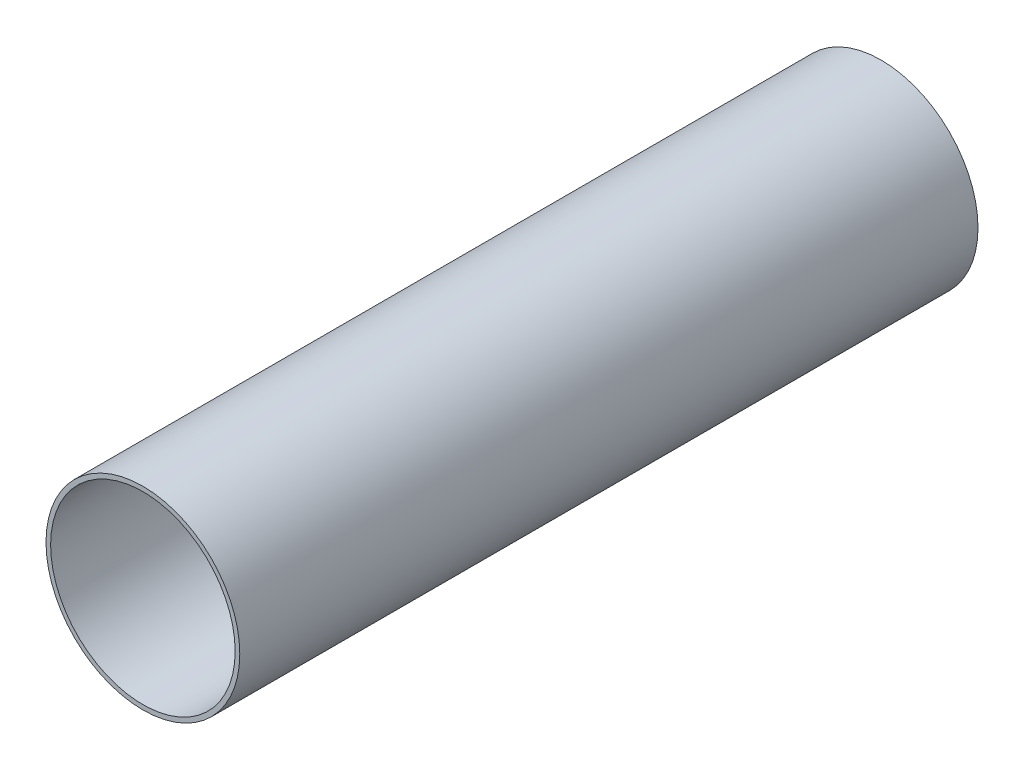
SolidWorks part; units mm, degrees
material "Corrugated Paper"
ref_plane "Front Plane" through (0, 0, 0) normal (0, 0, 1) x (1, 0, 0)
ref_plane "Top Plane" through (0, 0, 0) normal (0, 1, 0) x (1, 0, 0)
ref_plane "Right Plane" through (0, 0, 0) normal (1, 0, 0) x (0, 0, -1)
sketch "Sketch1" plane through (0, 0, 0) normal (0, 0, 1) x (1, 0, 0)
  circle A0 centre (0, 0) radius 50.8
  circle A1 centre (0, 0) radius 53.34
  dimension "D1" = 101.6
  dimension "D2" = 106.68
extrude "Boss-Extrude1" add sketch "Sketch1" along normal blind 406.4
